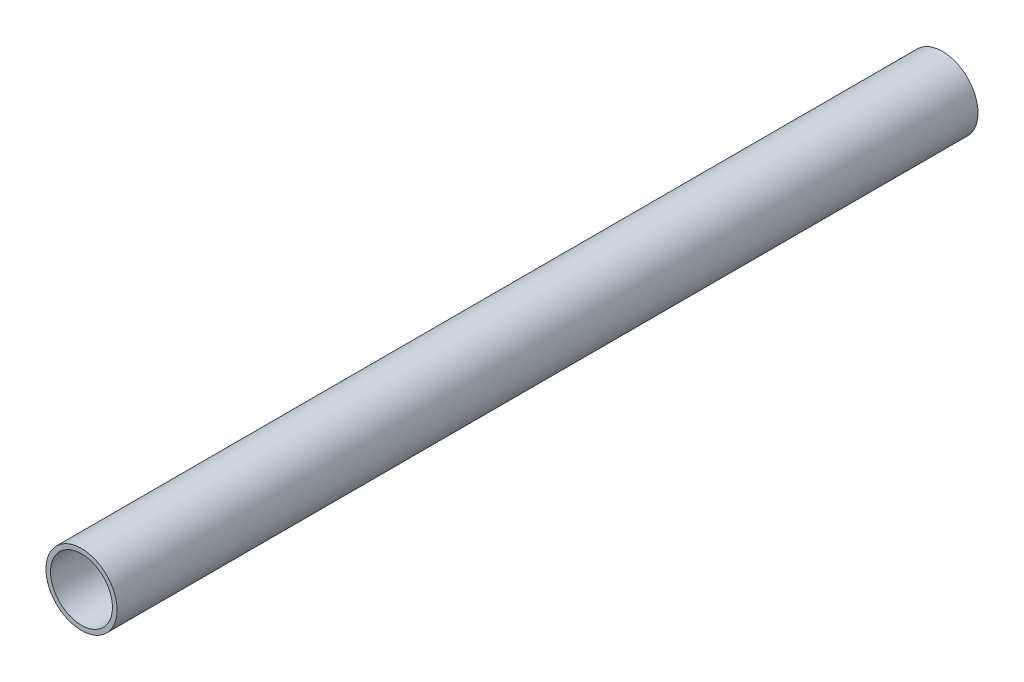
SolidWorks part; units mm, degrees
material "PVC Rigid"
ref_plane "Front Plane" through (0, 0, 0) normal (0, 0, 1) x (1, 0, 0)
ref_plane "Top Plane" through (0, 0, 0) normal (0, 1, 0) x (1, 0, 0)
ref_plane "Right Plane" through (0, 0, 0) normal (1, 0, 0) x (0, 0, -1)
sketch "Sketch1" plane through (0, 0, 0) normal (0, 0, 1) x (1, 0, 0)
  circle A0 centre (0, 0) radius 26.2509
  circle A1 centre (0, 0) radius 30.1625
  dimension "D1" = 60.325
  dimension "D2" = 3.9116
extrude "Boss-Extrude1" add sketch "Sketch1" along normal blind 730.25
